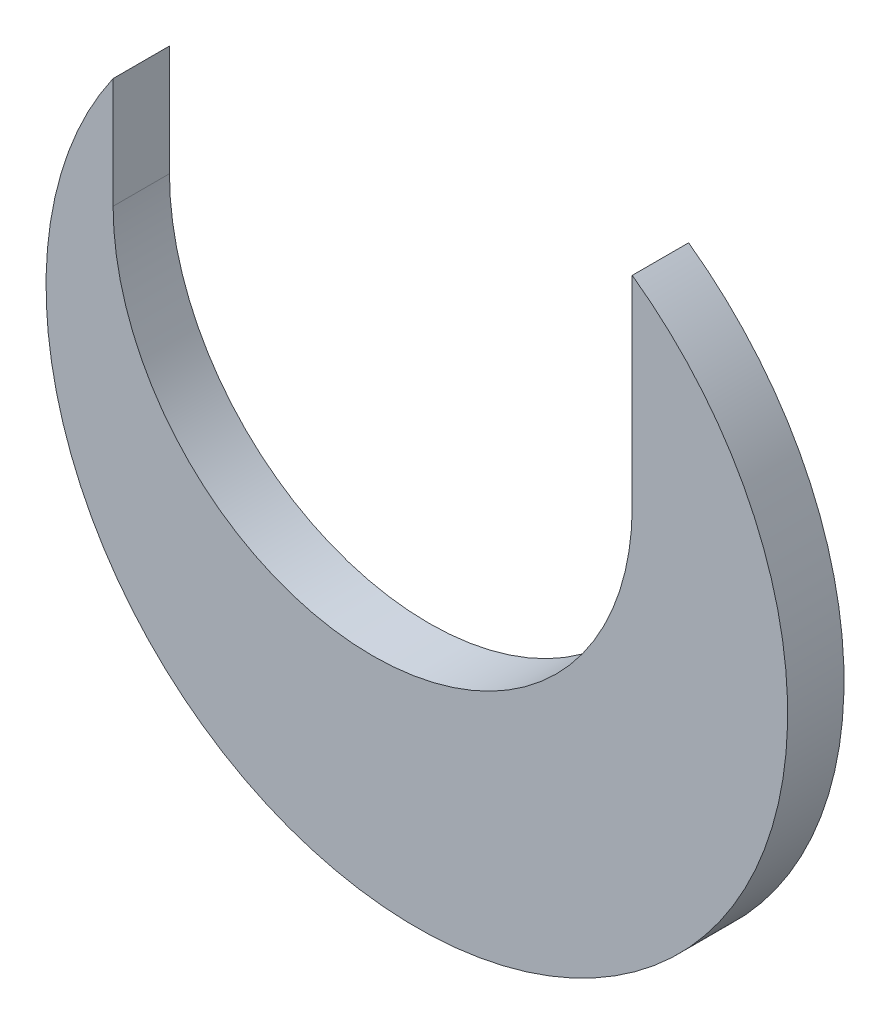
SolidWorks part; units mm, degrees
ref_plane "Front Plane" through (0, 0, 0) normal (0, 0, 1) x (1, 0, 0)
ref_plane "Top Plane" through (0, 0, 0) normal (0, 1, 0) x (1, 0, 0)
ref_plane "Right Plane" through (0, 0, 0) normal (1, 0, 0) x (0, 0, -1)
sketch "Sketch1" plane through (0, 0, 0) normal (0, 0, 1) x (1, 0, 0)
  line L0 (-26.0075, 8.7418) -> (-26.0075, 18.2119)
  line L1 (18.4425, 8.7418) -> (18.4425, 25.8445)
  circle A0 centre (0, 0) radius 31.75
  circle A1 centre (-3.7825, 8.7418) radius 22.225
  dimension "D1" = 44.45
  dimension "D2" = 63.5
extrude "Boss-Extrude1" add sketch "Sketch1" along normal blind 4.826 contours A1 L0 A0 L1
equation "\"MDF\"= 0.19in"
equation "\"PVCID\" = 2.067in"
equation "\"PVCOD\" = 2.375in"
equation "\"GenDiameter\"= 60mm"
equation "\"GenCutDiameter\" = 1.8in"
equation "\"GenCutDistance\" = 1"
equation "\"TowerHeight\" = 6in"
equation "\"TowerFrontBase\" = 3in"
equation "\"FunnelHeight\" = 1in"
equation "\"FunnelAngle\" = 20"
equation "\"TowerSideBase\" = 3in"
equation "\"TowerPanelLength\" = 2in"
equation "\"TowerPanelLeeway\" = 0.5in"
equation "\"BaseLength\" = 9in"
equation "\"BaseWidth\" = 10in"
equation "\"WheelHoleLength\" = 3.25in"
equation "\"WheelHoleWidth\" = 26mm"
equation "\"WheelHoleFromBack\" = 1.5in"
equation "\"DropLength\" = 1in"
equation "\"DropWidth\" = 8.5in"
equation "\"BumperWidth\" = 2in"
equation "\"SmallHexDiameter\" = 0.185in"
equation "\"SmallHexHeight\" = 0.701in"
equation "\"ScrewSize\" = 0.106in"
equation "\"BigHexDiameter\" = 0.251in"
equation "\"BigHexHeight\" = 0.374in"
equation "\"PCBThickness\" = 0.066in"
equation "\"ConnectorHeight\" = 0.517in"
equation "\"BoardHeight\" = 0.583in"
equation "\"UnoStackHeight\" = 1.351in"
equation "\"UnoStackWidth\" = 3.053in"
equation "\"UnoStackLength\" = 3.152in"
equation "\"HBridgeWidth\" = 1.797in"
equation "\"HBridgeLength\" = 2.236in"
equation "\"DSWidth\" = 1.820in"
equation "\"DSLength\" = 1.833in"
equation "\"StepperWidth\" = 1.799in"
equation "\"StepperLength\" = 2.248in"
equation "\"ULNWidth\" = 1.304in"
equation "\"ULNLength\" = 1.545in"
equation "\"VSwitchHeight\" = 0.392in"
equation "\"VSwitchWidth\" = 0.637in"
equation "\"VSwitchLength\" = 1.097in"
equation "\"SkateWheelDiameter\" = 80mm"
equation "\"SkateWheelThickness\" = 24mm"
equation "\"BaseDistance\" = 3in"
equation "\"DummyVar\" = 2in"
equation "\"D1@Boss-Extrude1\"=\"MDF\""
